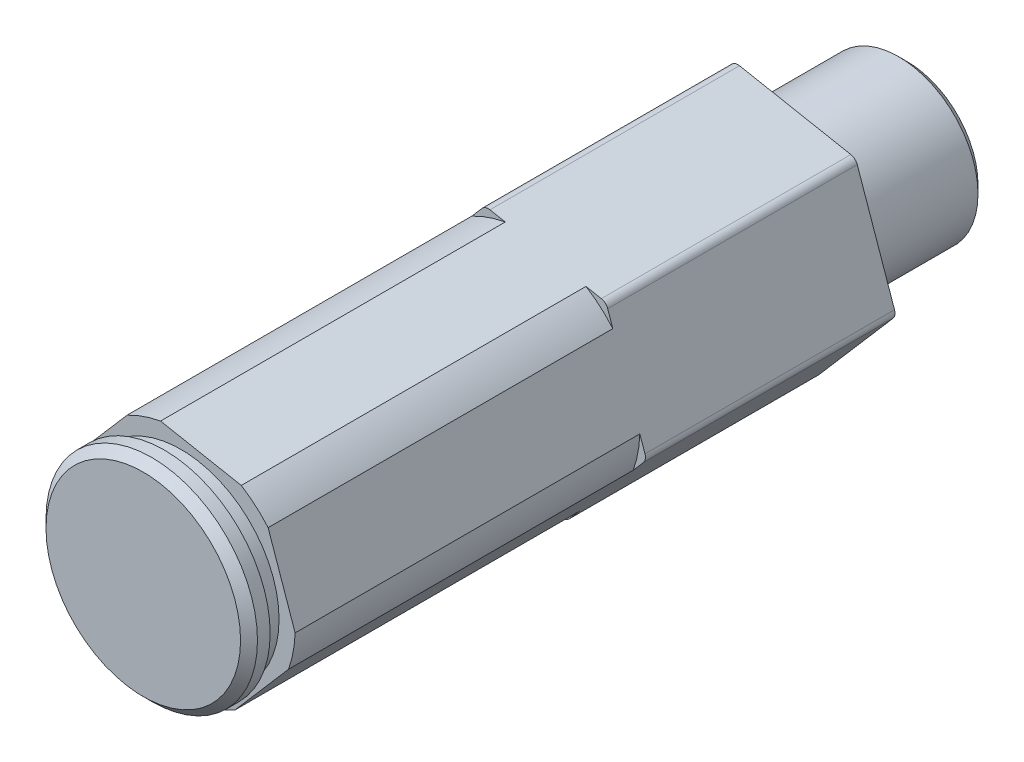
SolidWorks part; units mm, degrees
material "6061-T6 (SS)"
ref_plane "Front Plane" through (0, 0, 0) normal (0, 0, 1) x (1, 0, 0)
ref_plane "Top Plane" through (0, 0, 0) normal (0, 1, 0) x (1, 0, 0)
ref_plane "Right Plane" through (0, 0, 0) normal (1, 0, 0) x (0, 0, -1)
sketch "Sketch2" plane through (0, 0, 0) normal (1, 0, 0) x (0, 0, -1)
  line L0 (-22.9362, 0) -> (22.9362, 0)
  line L1 (22.9362, 0) -> (22.9362, 4.7625)
  line L6 (22.9362, 4.7625) -> (15.0114, 4.7625)
  line L7 (15.0114, 4.7625) -> (15.0114, 6.8623)
  line L8 (15.0114, 6.8623) -> (-20.6756, 6.8623)
  line L9 (-20.6756, 6.8623) -> (-20.6756, 5.8928)
  line L10 (-20.6756, 5.8928) -> (-21.6662, 5.8928)
  line L11 (-21.6662, 5.8928) -> (-21.6662, 6.35)
  line L12 (-21.6662, 6.35) -> (-22.9362, 6.35)
  line L13 (-22.9362, 6.35) -> (-22.9362, 0)
  line L14 (-34.6685, 0) -> (43.2094, 0) construction
  point P18 (0, 0)
  dimension "D1" = 35.687
  dimension "D2" = 7.9248
  dimension "D4" = 1.27
  dimension "D5" = 9.525
  dimension "D6" = 13.7246
  dimension "D7" = 11.7856
  dimension "D8" = 12.7
  dimension "D11" = 0.9906
revolve "Revolve1" add sketch "Sketch2" angle 360 about L0
sketch "Sketch3" plane through (0, 0, 22.9362) normal (0, 0, 1) x (1, 0, 0)
  line L1 (7.2629, -1.3857) -> (4.8315, 5.597)
  line L2 (4.8315, 5.597) -> (-2.4314, 6.9827)
  line L3 (-2.4314, 6.9827) -> (-7.2629, 1.3857)
  line L4 (-7.2629, 1.3857) -> (-4.8315, -5.597)
  line L5 (-4.8315, -5.597) -> (2.4314, -6.9827)
  line L6 (2.4314, -6.9827) -> (7.2629, -1.3857)
  circle A0 centre (0, 0) radius 6.4033 construction
  dimension "D1" = 12.8067
extrude "Cut-Extrude1" cut sketch "Sketch3" against normal through all flip side to cut
chamfer "Chamfer1" distance 0.508 angle 45 2 edges at (4.7625, 0, -22.9362) (6.35, 0, 22.9362)
sketch "Sketch4" plane through (0, 0, -15.0114) normal (0, 0, -1) x (-1, 0, 0)
  line L0 (-3.2348, -6.052) -> (-6.4595, -2.3164) construction
  line L1 (-2.4314, -6.9827) -> (4.8315, -5.597)
  line L2 (4.8315, -5.597) -> (7.2629, 1.3857)
  line L3 (7.2629, 1.3857) -> (2.4314, 6.9827)
  line L4 (2.4314, 6.9827) -> (-4.8315, 5.597)
  line L5 (-4.8315, 5.597) -> (-7.2629, -1.3857)
  line L6 (-7.2629, -1.3857) -> (-2.4314, -6.9827)
  line L9 (3.2348, 6.052) -> (6.4595, 2.3164) construction
  circle A0 centre (0, 0) radius 6.4033 construction
extrude "Boss-Extrude1" add sketch "Sketch4" against normal offset from surface (14.986 mm away) 20.701 up to face at (5.8928, 0, 20.6756)
fillet "Fillet1" radius 0.508 6 edges at (7.2629, -1.3857, -7.5184) (-2.4314, 6.9827, -7.5184) (-7.2629, 1.3857, -7.5184) (-4.8315, -5.597, -7.5184) (2.4314, -6.9827, -7.5184) (4.8315, 5.597, -7.5184)
